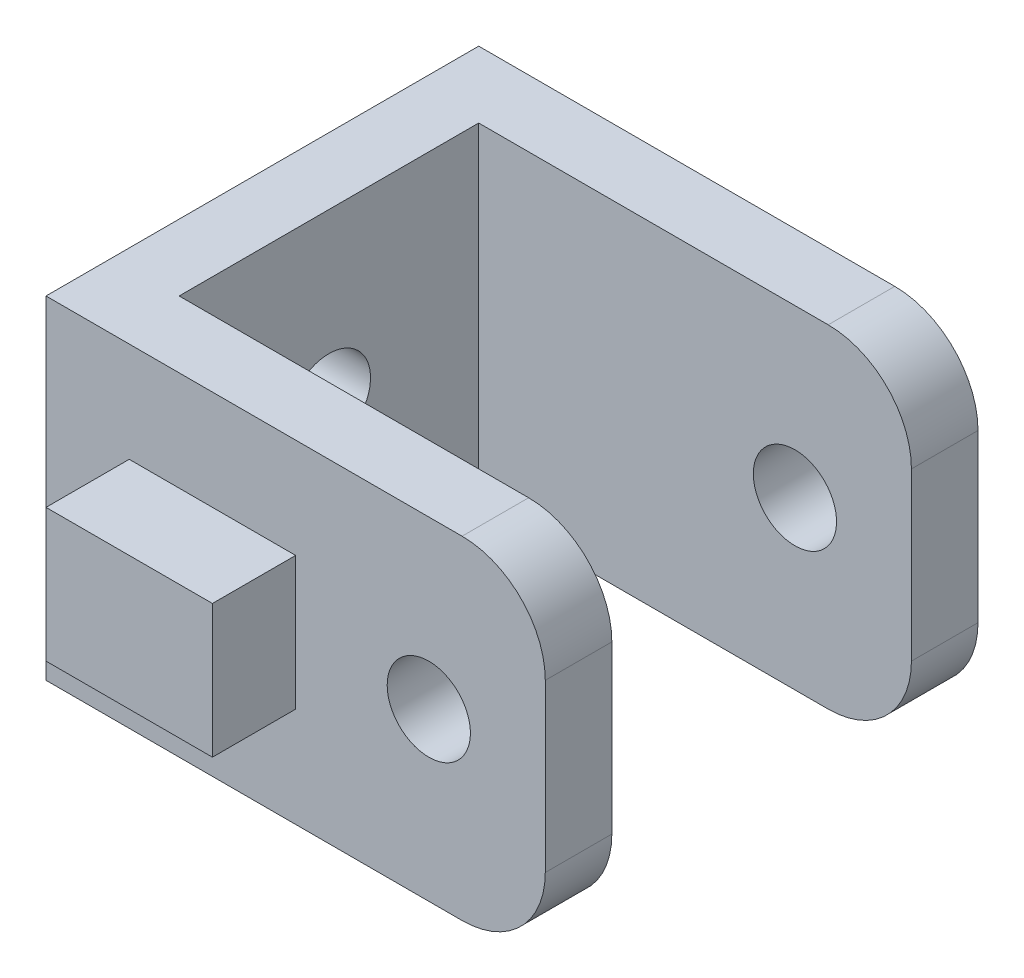
SolidWorks part; units mm, degrees
material "1060 Alloy"
ref_plane "前视基准面" through (0, 0, 0) normal (0, 0, 1) x (1, 0, 0)
ref_plane "上视基准面" through (0, 0, 0) normal (0, 1, 0) x (1, 0, 0)
ref_plane "右视基准面" through (0, 0, 0) normal (1, 0, 0) x (0, 0, -1)
sketch "Sketch1" plane through (0, 0, 0) normal (0, 1, 0) x (1, 0, 0)
  line L0 (-25.6779, 0) -> (55.2516, 0) construction
  line L1 (0, 13) -> (0, 0)
  line L2 (0, 13) -> (30, 13)
  line L3 (29.5723, 9) -> (30, 9)
  line L4 (4, 9) -> (4, 0)
  line L5 (4, 9) -> (29.5723, 9)
  line L6 (29.5723, 9) -> (39.1543, 6.9273)
  line L7 (30, 13) -> (40, 10.8369) construction
  line L8 (30, 9) -> (30, 13)
  line L9 (29.5723, -9) -> (30, -9)
  line L10 (4, -9) -> (4, 0)
  line L11 (4, -9) -> (29.5723, -9)
  line L12 (0, -13) -> (30, -13)
  line L13 (0, -13) -> (0, 0)
  line L14 (30, -9) -> (30, -13)
  dimension "D1" = 13
  dimension "D2" = 30
  dimension "D3" = 4
extrude "Boss-Extrude1" add sketch "Sketch1" along normal mid plane 20 contours L14 L9 L11 L10 L4 L5 L3 L8 L2 L1 L13 L12
sketch "Sketch2" plane through (0, 0, 13) normal (0, 0, 1) x (1, 0, 0)
  line L0 (-1.0263, 0) -> (31.921, 0) construction
fillet "Fillet1" radius 5 4 edges at (30, -10, -11) (30, -10, 11) (30, 10, -11) (30, 10, 11)
sketch "Sketch4" plane through (0, 0, 13) normal (0, 0, 1) x (1, 0, 0)
  line L0 (-1.0263, 0) -> (31.921, 0) construction
  line L1 (30, 5) -> (30, -5) construction
  line L2 (0, 10) -> (0, -10) construction
  line L3 (5, 4) -> (15, 4)
  line L4 (5, 4) -> (5, -4)
  line L5 (5, -4) -> (15, -4)
  line L6 (15, 4) -> (15, -4)
  line L7 (5, 4) -> (15, -4) construction
  line L8 (5, -4) -> (15, 4) construction
  circle A0 centre (23, 0) radius 10 construction
  point P6 (10, 0)
  dimension "D1" = 7
  dimension "D2" = 8
  dimension "D3" = 10
  dimension "D4" = 10
extrude "Boss-Extrude2" add sketch "Sketch4" along normal blind 5
sketch "Sketch5" plane through (0, 0, 13) normal (0, 0, 1) x (1, 0, 0)
  line L0 (-1.0263, 0) -> (31.921, 0) construction
  line L1 (30, 5) -> (30, -5) construction
  circle A0 centre (23, 0) radius 10 construction
  circle A1 centre (23, 0) radius 2.5
  dimension "D1" = 7
extrude "Cut-Extrude1" cut sketch "Sketch5" against normal up to surface and the other way through all up to face at (18.6785, 0, -13)
sketch "Sketch6" plane through (0, 0, -13) normal (0, 0, -1) x (-1, 0, 0)
  line L0 (1.0263, 0) -> (-31.921, 0) construction
  line L1 (-15, 4) -> (-5, 4)
  line L2 (-15, 4) -> (-15, -4)
  line L3 (-15, -4) -> (-5, -4)
  line L4 (-5, 4) -> (-5, -4)
  line L5 (-15, 4) -> (-5, -4) construction
  line L6 (-15, -4) -> (-5, 4) construction
  line L7 (0, 10) -> (0, -10) construction
  point P0 (-10, 0)
  dimension "D1" = 10
  dimension "D2" = 8
  dimension "D3" = 10
extrude "Boss-Extrude3" add sketch "Sketch6" along normal blind 5
sketch "Sketch7" plane through (0, 0, 0) normal (-1, 0, 0) x (0, 0, 1)
  circle A0 centre (0, 0) radius 2.5
extrude "Cut-Extrude2" cut sketch "Sketch7" against normal blind 5
